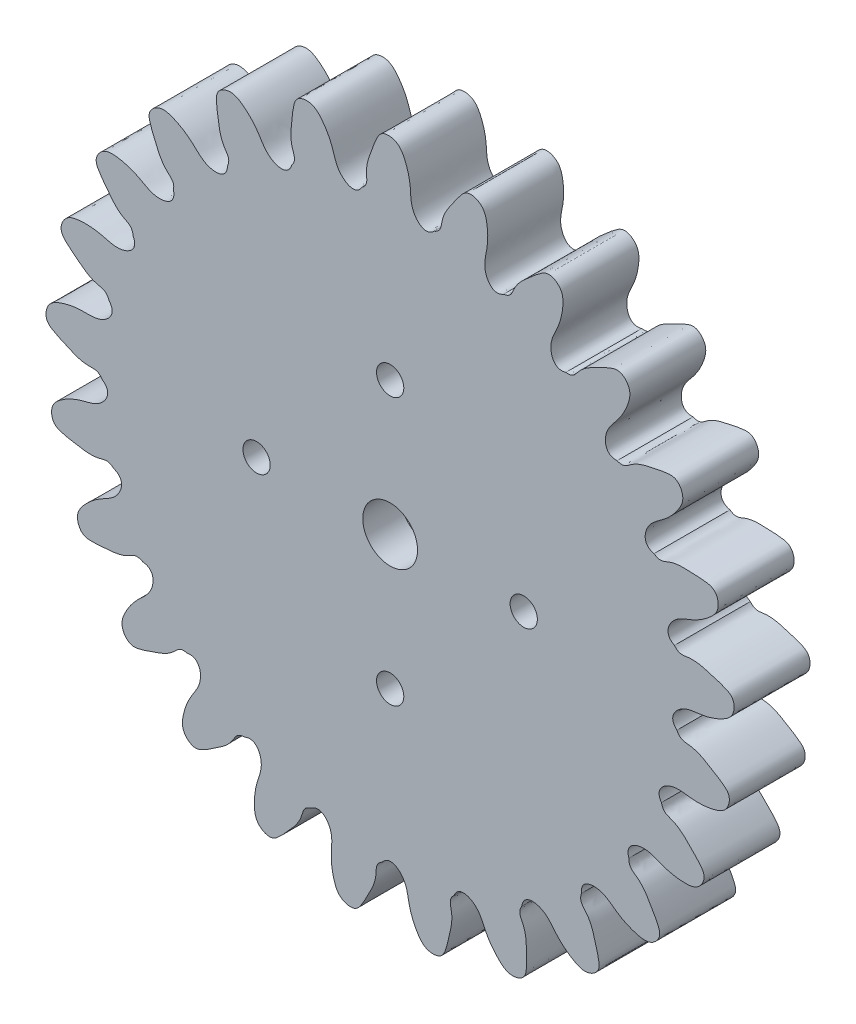
SolidWorks part; units mm, degrees
ref_plane "前视基准面" through (0, 0, 0) normal (0, 0, 1) x (1, 0, 0)
ref_plane "上视基准面" through (0, 0, 0) normal (0, 1, 0) x (1, 0, 0)
ref_plane "右视基准面" through (0, 0, 0) normal (1, 0, 0) x (0, 0, -1)
other "Configuration Table"
sketch "草图1" plane through (0, 0, 0) normal (0, 0, 1) x (1, 0, 0)
  line L0 (111.0606, 245.195) -> (531.0606, 245.195) construction
  circle A0 centre (68.3289, 56.2302) radius 23.7719
  spline S0 degree 3 poles (30.804, 53.5503) (30.8103, 54.2037) (30.2247, 55.7613) (28.0144, 55.4759) (26.1938, 56.1918) (24.4376, 56.9895) (22.7403, 57.9431) (23.0898, 60.1143) (25.1282, 61.1181) (27.4617, 61.5745) (30.4493, 61.2487) (32.3104, 63.1917) (31.2901, 64.3813) knots 0 0 0 0 0.103261 0.160728 0.279368 0.365488 0.432116 0.521173 0.596208 0.728852 0.843784 1 1 1 1
  spline S1 degree 3 poles (31.3147, 62.9706) (31.5281, 63.6058) (31.3118, 65.2658) (29.0947, 65.5149) (27.5086, 66.6741) (26.0051, 67.8804) (24.5984, 69.2269) (25.4768, 71.2429) (27.7009, 71.7082) (30.0756, 71.57) (32.8852, 70.5109) (35.1836, 71.9311) (34.4566, 73.339) knots 0 0 0 0 0.103726 0.161355 0.279919 0.36596 0.432531 0.521513 0.596482 0.729003 0.843829 1 1 1 1
  spline S2 degree 3 poles (34.1545, 71.9594) (34.4749, 72.529) (34.712, 74.1761) (32.6377, 74.9908) (31.3871, 76.4953) (30.2324, 78.0404) (29.2045, 79.6937) (30.5568, 81.4279) (32.8265, 81.3256) (35.0921, 80.6012) (37.5502, 78.877) (40.1291, 79.6809) (39.7756, 81.2251) knots 0 0 0 0 0.103258 0.160719 0.27935 0.365463 0.432085 0.521133 0.596162 0.728795 0.843717 1 1 1 1
  spline S3 degree 3 poles (39.1397, 79.964) (39.5918, 80.436) (40.2311, 81.9724) (38.4246, 83.2775) (37.5874, 85.0457) (36.8533, 86.8294) (36.2688, 88.6864) (38.0098, 90.0298) (40.1828, 89.3663) (42.1971, 88.1012) (44.1492, 85.8199) (46.847, 85.9572) (46.8886, 87.5407) knots 0 0 0 0 0.103263 0.160724 0.279354 0.365466 0.432088 0.521136 0.596164 0.728796 0.843718 1 1 1 1
  spline S4 degree 3 poles (45.9591, 86.4774) (46.5144, 86.8221) (47.5157, 88.1513) (46.0905, 89.8647) (45.7193, 91.7855) (45.4518, 93.6957) (45.3476, 95.6397) (47.368, 96.508) (49.3077, 95.3249) (50.9441, 93.5986) (52.2675, 90.9035) (54.9147, 90.3656) (55.3488, 91.889) knots 0 0 0 0 0.103263 0.160724 0.279354 0.365466 0.432088 0.521136 0.596164 0.728796 0.843718 1 1 1 1
  spline S5 degree 3 poles (54.1841, 91.0903) (54.8076, 91.2861) (56.108, 92.3245) (55.1537, 94.3384) (55.2719, 96.2913) (55.4879, 98.208) (55.8703, 100.1168) (58.0432, 100.4553) (59.6277, 98.8271) (60.7834, 96.748) (61.395, 93.8085) (63.8252, 92.6291) (64.6245, 93.9968) knots 0 0 0 0 0.103263 0.160724 0.279354 0.365466 0.432088 0.521136 0.596164 0.728796 0.843718 1 1 1 1
  spline S6 degree 3 poles (63.2978, 93.5127) (63.9504, 93.5473) (65.4682, 94.2297) (65.0447, 96.4177) (65.6449, 98.2798) (66.3307, 100.0826) (67.1759, 101.8364) (69.3647, 101.6239) (70.4945, 99.6527) (71.0968, 97.3515) (70.9582, 94.3523) (73.0188, 92.6056) (74.1331, 93.7315) knots 0 0 0 0 0.103263 0.160724 0.279354 0.365466 0.432088 0.521136 0.596164 0.728796 0.843718 1 1 1 1
  spline S7 degree 3 poles (72.7276, 93.5926) (73.3684, 93.4638) (75.0082, 93.7473) (75.1421, 95.9719) (76.1865, 97.6262) (77.2991, 99.2018) (78.5539, 100.6903) (80.6211, 99.9402) (81.2252, 97.7499) (81.2363, 95.3713) (80.3561, 92.5007) (81.9176, 90.2965) (83.2769, 91.1099) knots 0 0 0 0 0.103263 0.160724 0.279354 0.365466 0.432088 0.521136 0.596164 0.728796 0.843718 1 1 1 1
  spline S8 degree 3 poles (81.8811, 91.3249) (82.4697, 91.0408) (84.1285, 90.9076) (84.8114, 93.029) (86.2344, 94.3716) (87.7039, 95.621) (89.2894, 96.7506) (91.1051, 95.51) (91.1456, 93.2383) (90.5648, 90.9316) (88.9984, 88.3702) (89.9626, 85.8468) (91.4815, 86.2967) knots 0 0 0 0 0.103263 0.160724 0.279354 0.365466 0.432088 0.521136 0.596164 0.728796 0.843718 1 1 1 1
  spline S9 degree 3 poles (90.183, 86.852) (90.6824, 86.4305) (92.256, 85.8889) (93.4451, 87.7738) (95.1572, 88.7204) (96.8913, 89.5651) (98.7079, 90.2649) (100.158, 88.6117) (99.6323, 86.4014) (98.4961, 84.3116) (96.3419, 82.2202) (96.6483, 79.5363) (98.2314, 79.5942) knots 0 0 0 0 0.103263 0.160724 0.279354 0.365466 0.432088 0.521136 0.596164 0.728796 0.843718 1 1 1 1
  spline S10 degree 3 poles (97.1118, 80.4551) (97.4907, 79.9226) (98.8801, 79.0067) (100.5006, 80.5367) (102.3943, 81.0277) (104.284, 81.4146) (106.2176, 81.6407) (107.211, 79.6788) (106.1521, 77.6687) (104.5319, 75.9271) (101.9252, 74.4371) (101.5546, 71.7613) (103.1023, 71.4238) knots 0 0 0 0 0.103263 0.160724 0.279354 0.365466 0.432088 0.521136 0.596164 0.728796 0.843718 1 1 1 1
  spline S11 degree 3 poles (102.232, 72.536) (102.4665, 71.926) (103.5846, 70.6934) (105.5346, 71.7723) (107.491, 71.7769) (109.4175, 71.6817) (111.3466, 71.4199) (111.8209, 69.2726) (110.2953, 67.5889) (108.2929, 66.305) (105.3976, 65.51) (104.3732, 63.0105) (105.7883, 62.2986) knots 0 0 0 0 0.103263 0.160724 0.279354 0.365466 0.432088 0.521136 0.596164 0.728796 0.843718 1 1 1 1
  spline S12 degree 3 poles (105.2219, 63.5924) (105.2974, 62.9432) (106.0738, 61.4712) (108.2309, 62.0313) (110.127, 61.5493) (111.9692, 60.978) (113.7726, 60.2446) (113.698, 58.0468) (111.8016, 56.7954) (109.5429, 56.0498) (106.5408, 55.9998) (104.9269, 53.8336) (106.1206, 52.7922) knots 0 0 0 0 0.103263 0.160724 0.279354 0.365466 0.432088 0.521136 0.596164 0.728796 0.843718 1 1 1 1
  spline S13 degree 3 poles (105.8938, 54.1861) (105.8054, 53.5386) (106.1913, 51.9198) (108.4199, 51.9258) (110.1366, 50.9874) (111.7789, 49.9759) (113.3432, 48.8171) (112.7244, 46.7069) (110.5764, 45.9664) (108.2032, 45.806) (105.283, 46.5042) (103.1811, 44.8073) (104.0783, 43.5018) knots 0 0 0 0 0.103263 0.160724 0.279354 0.365466 0.432088 0.521136 0.596164 0.728796 0.843718 1 1 1 1
  spline S14 degree 3 poles (104.2052, 44.9084) (103.9586, 44.3031) (103.9299, 42.6392) (106.0899, 42.0908) (107.5193, 40.755) (108.8585, 39.3668) (110.0855, 37.8553) (108.9613, 35.9653) (106.6966, 35.7823) (104.358, 36.2171) (101.7033, 37.6196) (99.2454, 36.4988) (99.7897, 35.0112) knots 0 0 0 0 0.103263 0.160724 0.279354 0.365466 0.432088 0.521136 0.596164 0.728796 0.843718 1 1 1 1
  spline S15 degree 3 poles (100.2625, 36.342) (99.8731, 35.8171) (99.4314, 34.2126) (101.3873, 33.1442) (102.4395, 31.4949) (103.3914, 29.8173) (104.2039, 28.0482) (102.6451, 26.4971) (100.4061, 26.8831) (98.2491, 27.8858) (96.0265, 29.9044) (93.3671, 29.4301) (93.5244, 27.8538) knots 0 0 0 0 0.103263 0.160724 0.279354 0.365466 0.432088 0.521136 0.596164 0.728796 0.843718 1 1 1 1
  spline S16 degree 3 poles (94.3132, 29.0252) (93.8055, 28.6137) (92.9787, 27.1694) (94.6074, 25.6482) (95.2164, 23.789) (95.7212, 21.9274) (96.0683, 20.0118) (94.1726, 18.8972) (92.1, 19.8278) (90.2601, 21.3354) (88.6093, 23.8434) (85.9156, 24.0453) (85.6759, 22.4794) knots 0 0 0 0 0.103263 0.160724 0.279354 0.365466 0.432088 0.521136 0.596164 0.728796 0.843718 1 1 1 1
  spline S17 degree 3 poles (86.7313, 23.4179) (86.1372, 23.1455) (84.9772, 21.9523) (86.1764, 20.0738) (86.3039, 18.1216) (86.3299, 16.1929) (86.1896, 14.2512) (84.0764, 13.643) (82.3002, 15.0598) (80.8931, 16.9777) (79.9179, 19.8173) (77.359, 20.6828) (76.7374, 19.2257) knots 0 0 0 0 0.103263 0.160724 0.279354 0.365466 0.432088 0.521136 0.596164 0.728796 0.843718 1 1 1 1
  spline S18 degree 3 poles (77.993, 19.8723) (77.3499, 19.7562) (75.9296, 18.8889) (76.624, 16.7712) (76.262, 14.8486) (75.8074, 12.9741) (75.1887, 11.1282) (72.9906, 11.0647) (71.6226, 12.8787) (70.7366, 15.0863) (70.4983, 18.0792) (68.235, 19.5539) (67.2706, 18.2972) knots 0 0 0 0 0.103263 0.160724 0.279354 0.365466 0.432088 0.521136 0.596164 0.728796 0.843718 1 1 1 1
  spline S19 degree 3 poles (68.6476, 18.6111) (67.9957, 18.6586) (66.4044, 18.1718) (66.5503, 15.948) (65.7215, 14.1758) (64.8151, 12.4732) (63.7568, 10.8392) (61.6119, 11.3243) (60.7381, 13.4216) (60.4289, 15.7801) (60.9424, 18.7383) (59.1169, 20.7295) (57.8703, 19.7521) knots 0 0 0 0 0.103263 0.160724 0.279354 0.365466 0.432088 0.521136 0.596164 0.728796 0.843718 1 1 1 1
  spline S20 degree 3 poles (59.2821, 19.7138) (58.6625, 19.9219) (57.0001, 19.8461) (56.5884, 17.6559) (55.3449, 16.1455) (54.0436, 14.7218) (52.6122, 13.4023) (50.6553, 14.4056) (50.3305, 16.6543) (50.6176, 19.0155) (51.8506, 21.7531) (50.5777, 24.1357) (49.1271, 23.4991) knots 0 0 0 0 0.103263 0.160724 0.279354 0.365466 0.432088 0.521136 0.596164 0.728796 0.843718 1 1 1 1
  spline S21 degree 3 poles (50.485, 23.1108) (49.9367, 23.4665) (48.3077, 23.8065) (47.3642, 21.7875) (45.7842, 20.6338) (44.1697, 19.5784) (42.4551, 18.6564) (40.8092, 20.1148) (41.0538, 22.3736) (41.9191, 24.5893) (43.7942, 26.9343) (43.1538, 29.5586) (41.5905, 29.3027) knots 0 0 0 0 0.103263 0.160724 0.279354 0.365466 0.432088 0.521136 0.596164 0.728796 0.843718 1 1 1 1
  spline S22 degree 3 poles (42.8091, 28.5889) (42.3665, 29.0698) (40.8732, 29.8043) (39.4573, 28.0833) (37.64, 27.3587) (35.8137, 26.7381) (33.9237, 26.2714) (32.6922, 28.0933) (33.4909, 30.2203) (34.88, 32.1512) (37.2794, 33.9562) (37.3117, 36.6573) (35.7339, 36.7982) knots 0 0 0 0 0.103263 0.160724 0.279354 0.365466 0.432088 0.521136 0.596164 0.728796 0.843718 1 1 1 1
  spline S23 degree 3 poles (36.7368, 35.8038) (36.4276, 36.3797) (35.1639, 37.4624) (33.3645, 36.1476) (31.4241, 35.8978) (29.5009, 35.7508) (27.5541, 35.7688) (26.8145, 37.8398) (28.117, 39.7013) (29.9427, 41.2261) (32.7155, 42.3777) (33.4186, 44.9859) (31.9254, 45.5148) knots 0 0 0 0 0.103263 0.160724 0.279354 0.365467 0.432088 0.521136 0.596164 0.728797 0.843718 1 1 1 1
  spline S24 degree 3 poles (32.6495, 44.3022) (32.4932, 44.9368) (31.5385, 46.2998) (29.4686, 45.4739) (27.5271, 45.7144) (25.6277, 46.0503) (23.7466, 46.5519) (23.5452, 48.7417) (25.2698, 50.2209) (27.4173, 51.2438) (30.3893, 51.6696) (31.719, 54.0208) (30.4043, 54.9044) knots 0 0 0 0 0.103264 0.160725 0.279356 0.36547 0.432092 0.521142 0.59617 0.728804 0.843727 1 1 1 1
  point P330 (68.3289, 56.2302)
extrude "凸台-拉伸1" add sketch "草图1" along normal blind 10 contours S24 S23 S22 S21 S20 S19 S18 S17 S16 S15 S14 S13 S12 S11 S10 S9 S8 S7 S6 S5 S4 S3 S2 S1 S0 A0
ref_plane "基准面1" through (0, 0, 5) normal (0, 0, 1) x (1, 0, 0)
sketch "草图2" plane through (0, 0, 5) normal (0, 0, 1) x (1, 0, 0)
  circle A0 centre (68.3289, 56.2302) radius 23.7719
extrude "凸台-拉伸2" add sketch "草图2" along normal blind 5
sketch "草图3" plane through (0, 0, 5) normal (0, 0, -1) x (-1, 0, 0)
  line L0 (-71.9412, 56.2302) -> (-37.6176, 56.2302) construction
  line L1 (-68.3289, 52.6179) -> (-68.3289, 59.8426) construction
  circle A0 centre (-68.3289, 56.2302) radius 3.6123
  circle A1 centre (-68.3289, 73.8311) radius 1.7971
  circle A2 centre (-50.728, 56.2302) radius 1.7971
  circle A3 centre (-68.3289, 38.6294) radius 1.7971
  circle A4 centre (-85.9297, 56.2302) radius 1.7971
  point P18 (-68.3289, 56.2302)
  dimension "D1" = 4
extrude "切除-拉伸1" cut sketch "草图3" against normal through all
